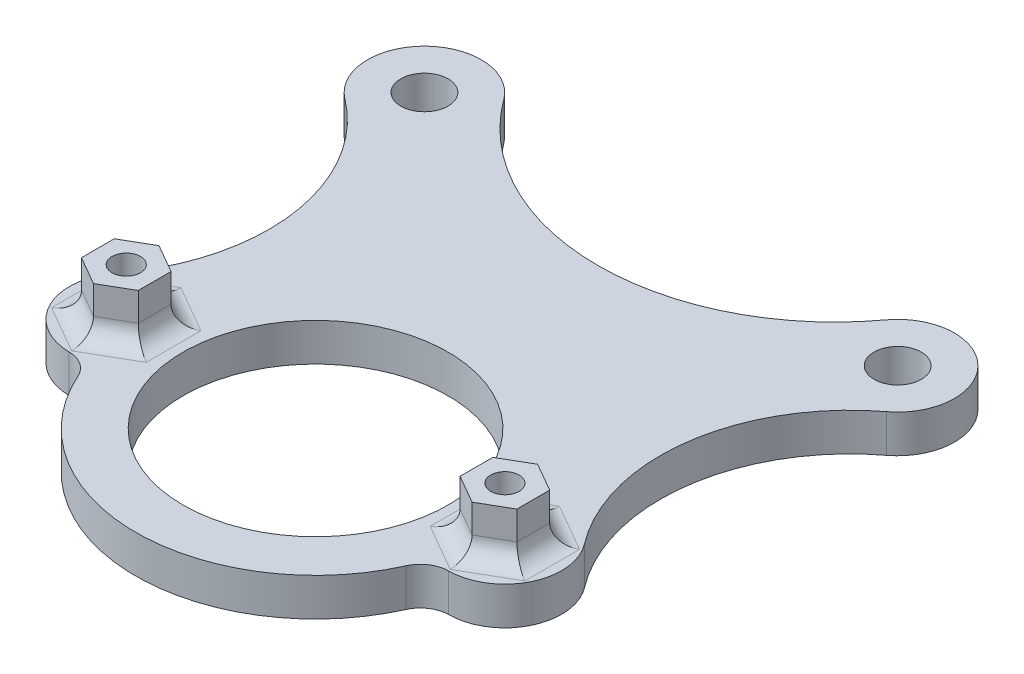
SolidWorks part; units mm, degrees
material "Plain Carbon Steel"
ref_plane "Front Plane" through (0, 0, 0) normal (0, 0, 1) x (1, 0, 0)
ref_plane "Top Plane" through (0, 0, 0) normal (0, 1, 0) x (1, 0, 0)
ref_plane "Right Plane" through (0, 0, 0) normal (1, 0, 0) x (0, 0, -1)
sketch "Sketch1" plane through (0, 0, 0) normal (0, 1, 0) x (1, 0, 0)
  line L0 (0, 0) -> (0, 45.6397) construction
  line L1 (8.1269, 17.1742) -> (19.5886, 33.9083)
  line L2 (0, 0) -> (25, 36.5) construction
  line L3 (13.0771, 13.7837) -> (24.5388, 30.5178)
  line L4 (-13.0771, 13.7837) -> (-24.5388, 30.5178)
  line L5 (-8.1269, 17.1742) -> (-19.5886, 33.9083)
  circle A0 centre (0, 0) radius 14
  arc A1 (18.125, -5.6995) -> (18.125, 5.6995) centre (20, 0) ccw
  arc A2 (0, -19) -> (18.125, -5.6995) centre (0, 0) ccw
  arc A3 (-8.1269, 17.1742) -> (8.1269, 17.1742) centre (0, 0) cw
  arc A4 (24.5388, 30.5178) -> (19.5886, 33.9083) centre (25, 36.5) ccw
  circle A5 centre (25, 36.5) radius 2.5
  arc A6 (13.0771, 13.7837) -> (18.125, 5.6995) centre (0, 0) cw
  arc A7 (0, -19) -> (-18.125, -5.6995) centre (0, 0) cw
  arc A8 (-18.125, -5.6995) -> (-18.125, 5.6995) centre (-20, 0) cw
  arc A9 (-13.0771, 13.7837) -> (-18.125, 5.6995) centre (0, 0) ccw
  arc A10 (-24.5388, 30.5178) -> (-19.5886, 33.9083) centre (-25, 36.5) cw
  circle A11 centre (-25, 36.5) radius 2.5
  point P33 (0, 0)
  dimension "D2" = 28
  dimension "D3" = 19
  dimension "D4" = 5
  dimension "D5" = 6
  dimension "D1" = 12
  dimension "D6" = 50
  dimension "D7" = 40
  dimension "D8" = 36.5
extrude "Boss-Extrude1" add sketch "Sketch1" along normal blind 4
fillet "Fillet1" radius 3 11 edges at (-19.5886, 2, -33.9083) (-8.1269, 2, -17.1742) (19.5886, 2, -33.9083) (8.1269, 2, -17.1742) (13.0771, 2, -13.7837) (24.5388, 2, -30.5178) (18.125, 2, 5.6995) (-18.125, 2, 5.6995) (-18.125, 2, -5.6995) (-24.5388, 2, -30.5178) (-13.0771, 2, -13.7837)
sketch "Sketch2" plane through (0, 4, 0) normal (0, 1, 0) x (1, 0, 0)
  line L0 (0, 0) -> (0, -5.9832) construction
  circle A0 centre (20, 0) radius 1.5
  circle A1 centre (-20, 0) radius 1.5
  dimension "D1" = 40
  dimension "D2" = 3
extrude "Cut-Extrude1" cut sketch "Sketch2" against normal blind 10
sketch "Sketch3" plane through (0, 4, 0) normal (0, 1, 0) x (1, 0, 0)
  line L1 (-20, 3.4641) -> (-23, 1.7321)
  line L2 (-23, 1.7321) -> (-23, -1.7321)
  line L3 (-23, -1.7321) -> (-20, -3.4641)
  line L4 (-20, -3.4641) -> (-17, -1.7321)
  line L5 (-17, -1.7321) -> (-17, 1.7321)
  line L6 (-17, 1.7321) -> (-20, 3.4641)
  line L7 (20, 3.4641) -> (17, 1.7321)
  line L8 (17, 1.7321) -> (17, -1.7321)
  line L9 (17, -1.7321) -> (20, -3.4641)
  line L10 (20, -3.4641) -> (23, -1.7321)
  line L11 (23, -1.7321) -> (23, 1.7321)
  line L12 (23, 1.7321) -> (20, 3.4641)
  circle A0 centre (-20, 0) radius 3 construction
  circle A1 centre (20, 0) radius 3 construction
  circle A2 centre (-20, 0) radius 1.5 construction
  circle A3 centre (-20, 0) radius 1.5
  circle A4 centre (20, 0) radius 1.5 construction
  circle A5 centre (20, 0) radius 1.5
  dimension "D1" = 6
extrude "Boss-Extrude2" add sketch "Sketch3" along normal blind 5
fillet "Fillet2" radius 2 12 edges at (18.5, 4, 2.5981) (17, 4, 0) (18.5, 4, -2.5981) (21.5, 4, 2.5981) (23, 4, 0) (21.5, 4, -2.5981) (-17, 4, 0) (-18.5, 4, 2.5981) (-21.5, 4, 2.5981) (-23, 4, 0) (-21.5, 4, -2.5981) (-18.5, 4, -2.5981)
sketch "Sketch4" plane through (0, 4, 0) normal (0, 1, 0) x (1, 0, 0)
  line L0 (0, 19) -> (0, 0) construction
  arc A0 (24.7721, 3.6369) -> (28.6183, 31.7138) centre (40.6793, 15.7597) cw
  arc A1 (20.05, -5.9998) -> (18.125, 5.6995) centre (20, 0) ccw construction
  arc A2 (25.773, 30.55) -> (19.1727, 35.0707) centre (25, 36.5) ccw construction
  arc A3 (20.1613, 40.0478) -> (-20.1613, 40.0478) centre (0, 54.8303) cw
  arc A4 (-19.1727, 35.0707) -> (-25.773, 30.55) centre (-25, 36.5) ccw construction
  arc A5 (6.0545, 18.0095) -> (-6.0545, 18.0095) centre (0, 0) ccw construction
  arc A6 (28.6183, 31.7138) -> (20.1613, 40.0478) centre (25.7324, 37.2432) cw
  arc A7 (24.7721, 3.6369) -> (15.4158, 6.3386) centre (23.133, 15.5123) cw
  arc A8 (15.4158, 6.3386) -> (0, 15.8021) centre (0.0285, -1.4391) ccw
  arc A9 (20.05, -5.9998) -> (18.125, 5.6995) centre (20, 0) ccw construction
  arc A10 (-15.4158, 6.3386) -> (0, 15.8021) centre (-0.0285, -1.4391) cw
  arc A11 (-24.7721, 3.6369) -> (-15.4158, 6.3386) centre (-23.133, 15.5123) ccw
  arc A12 (-24.7721, 3.6369) -> (-28.6183, 31.7138) centre (-40.6793, 15.7597) ccw
  arc A13 (-28.6183, 31.7138) -> (-20.1613, 40.0478) centre (-25.7324, 37.2432) ccw
  point P36 (21.3544, 32.8006)
  dimension "D1" = 25
  dimension "D2" = 20
extrude "Boss-Extrude3" add sketch "Sketch4" against normal blind 4
